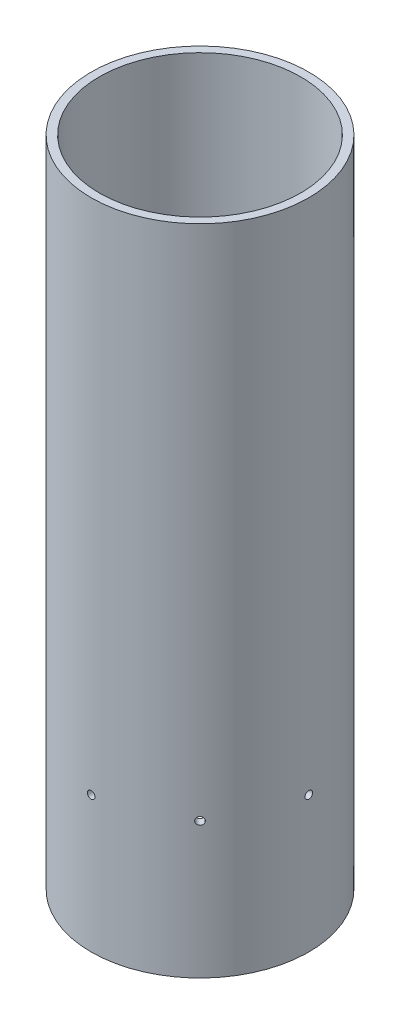
SolidWorks part; units mm, degrees
material "Glass"
ref_plane "Front Plane" through (0, 0, 0) normal (0, 0, 1) x (1, 0, 0)
ref_plane "Top Plane" through (0, 0, 0) normal (0, 1, 0) x (1, 0, 0)
ref_plane "Right Plane" through (0, 0, 0) normal (1, 0, 0) x (0, 0, -1)
sketch "Sketch1" plane through (0, 0, 0) normal (0, 1, 0) x (1, 0, 0)
  circle A0 centre (0, 0) radius 50.8
  circle A1 centre (0, 0) radius 46.99
  dimension "D1" = 101.6
  dimension "D2" = 93.98
extrude "Boss-Extrude1" add sketch "Sketch1" along normal blind 304.8
ref_plane "Plane1" through (50.8, 0, 0) normal (1, 0, 0) x (0, 0, -1)
sketch "Sketch2" plane through (50.8, 0, 0) normal (1, 0, 0) x (0, 0, -1)
  line L0 (-46.99, 0) -> (46.99, 0) construction
  line L1 (0, 63.5) -> (0, 0) construction
  line L2 (-50.8, 0) -> (50.8, 0) construction
  circle A0 centre (0, 63.5) radius 1.7526
  dimension "D2" = 3.5052
  dimension "D1" = 63.5
extrude "Bulkhead Holes" cut sketch "Sketch2" against normal up to next
pattern_circular "Bulkhead Hole Pattern" count 8 over 360 about axis through (0, 0, 0) along (0, 1, 0) of "Bulkhead Holes"
